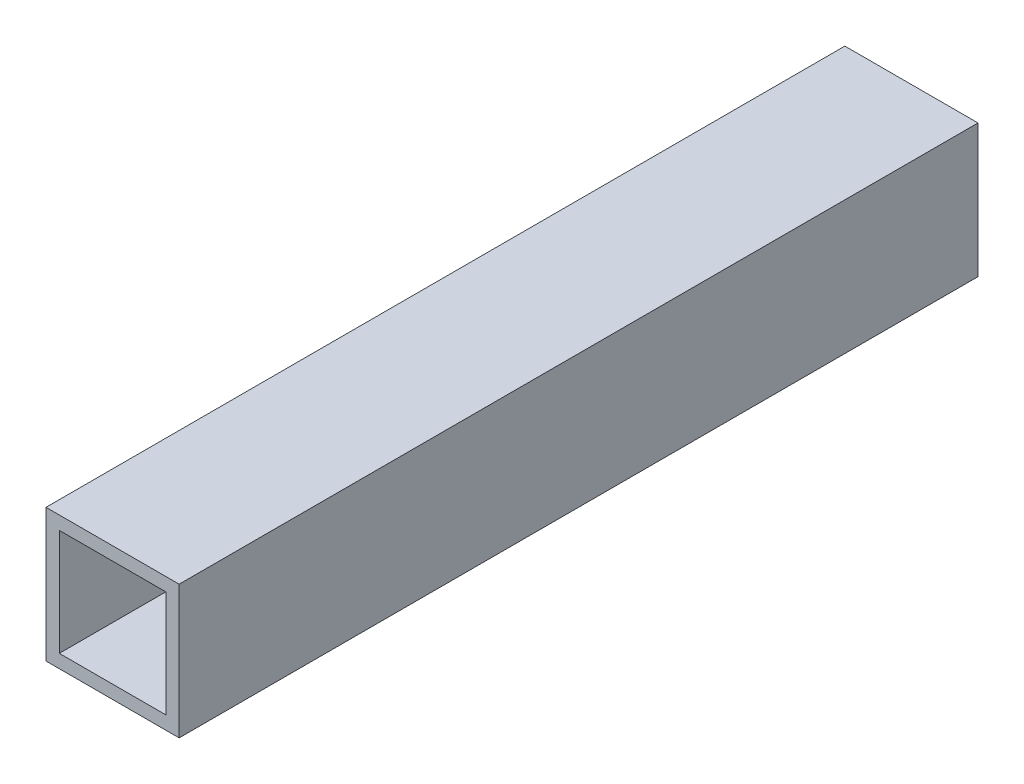
SolidWorks part; units mm, degrees
ref_plane "Plan de face" through (0, 0, 0) normal (0, 0, 1) x (1, 0, 0)
ref_plane "Plan de dessus" through (0, 0, 0) normal (0, 1, 0) x (1, 0, 0)
ref_plane "Plan de droite" through (0, 0, 0) normal (1, 0, 0) x (0, 0, -1)
sketch "Esquisse1" plane through (0, 0, 0) normal (0, 0, 1) x (1, 0, 0)
  line L1 (-7.5, -7.5) -> (7.5, -7.5)
  line L2 (-7.5, -7.5) -> (-7.5, 7.5)
  line L3 (-7.5, 7.5) -> (7.5, 7.5)
  line L4 (7.5, -7.5) -> (7.5, 7.5)
  line L5 (-7.5, -7.5) -> (7.5, 7.5) construction
  line L6 (-7.5, 7.5) -> (7.5, -7.5) construction
  point P0 (0, 0)
  dimension "D1" = 15
  dimension "D2" = 15
extrude "Extrusion1" add sketch "Esquisse1" along normal blind 90
sketch "Esquisse2" plane through (0, 0, 90) normal (0, 0, 1) x (1, 0, 0)
  line L0 (7.5, 7.5) -> (-7.5, 7.5) construction
  line L1 (-6, -6) -> (6, -6)
  line L2 (-6, -6) -> (-6, 6)
  line L3 (-6, 6) -> (6, 6)
  line L4 (6, -6) -> (6, 6)
  line L5 (-6, -6) -> (6, 6) construction
  line L6 (-6, 6) -> (6, -6) construction
  line L7 (7.5, -7.5) -> (7.5, 7.5) construction
  point P0 (0, 0)
  dimension "D1" = 1.5
  dimension "D2" = 1.5
extrude "Extrusion2" cut sketch "Esquisse2" against normal through all
